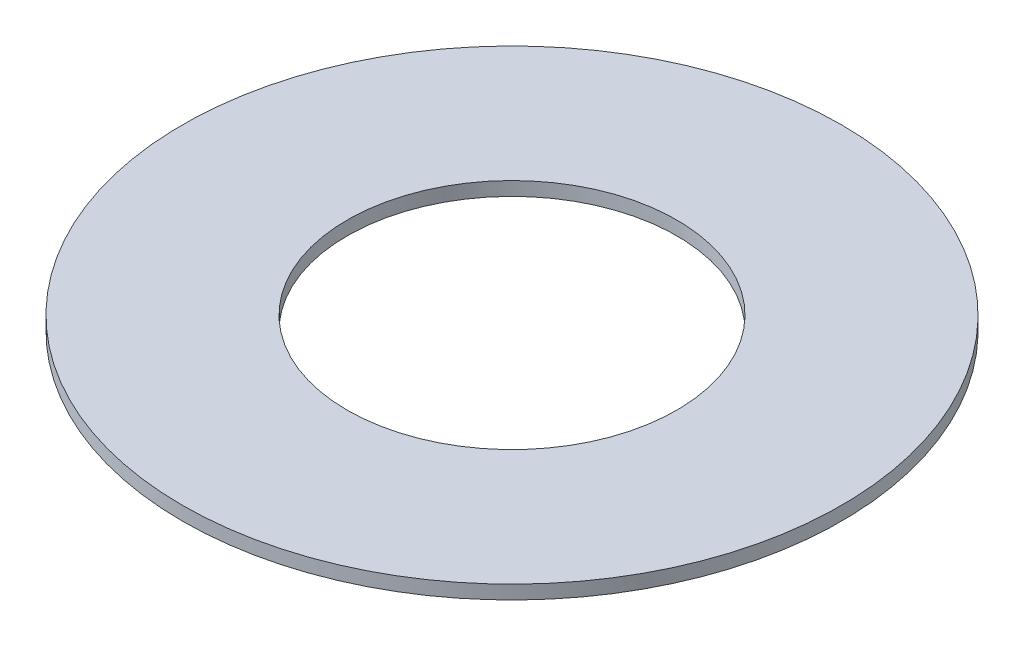
SolidWorks part; units mm, degrees
ref_plane "Front Plane" through (0, 0, 0) normal (0, 0, 1) x (1, 0, 0)
ref_plane "Top Plane" through (0, 0, 0) normal (0, 1, 0) x (1, 0, 0)
ref_plane "Right Plane" through (0, 0, 0) normal (1, 0, 0) x (0, 0, -1)
sketch "Sketch1" plane through (0, 0, 0) normal (0, 1, 0) x (1, 0, 0)
  circle A0 centre (0, 0) radius 10.3124
  circle A1 centre (0, 0) radius 5.1562
  dimension "D1" = 20.6248
  dimension "D2" = 10.3124
extrude "Boss-Extrude1" add sketch "Sketch1" along normal blind 0.43
